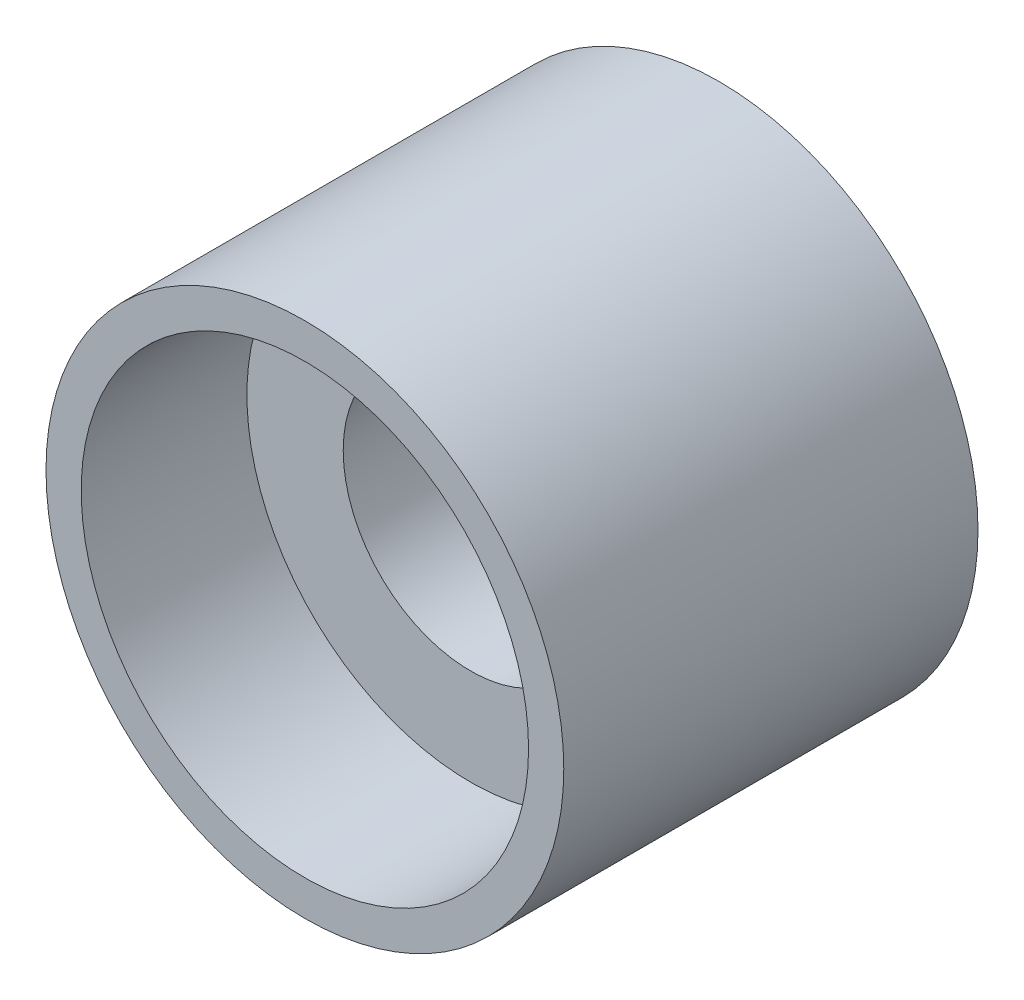
SolidWorks part; units mm, degrees
ref_plane "Front Plane" through (0, 0, 0) normal (0, 0, 1) x (1, 0, 0)
ref_plane "Top Plane" through (0, 0, 0) normal (0, 1, 0) x (1, 0, 0)
ref_plane "Right Plane" through (0, 0, 0) normal (1, 0, 0) x (0, 0, -1)
sketch "Sketch1" plane through (0, 0, 0) normal (0, 0, 1) x (1, 0, 0)
  circle A0 centre (0, 0) radius 12.5
  circle A1 centre (0, 0) radius 6.15
  dimension "D1" = 25
  dimension "D2" = 12.3
extrude "Boss-Extrude1" add sketch "Sketch1" along normal blind 20
sketch "Sketch2" plane through (0, 0, 20) normal (0, 0, 1) x (1, 0, 0)
  circle A0 centre (0, 0) radius 10.8
  circle A1 centre (0, 0) radius 12.5 construction
  dimension "D1" = 1.7
extrude "Cut-Extrude1" cut sketch "Sketch2" against normal blind 8
